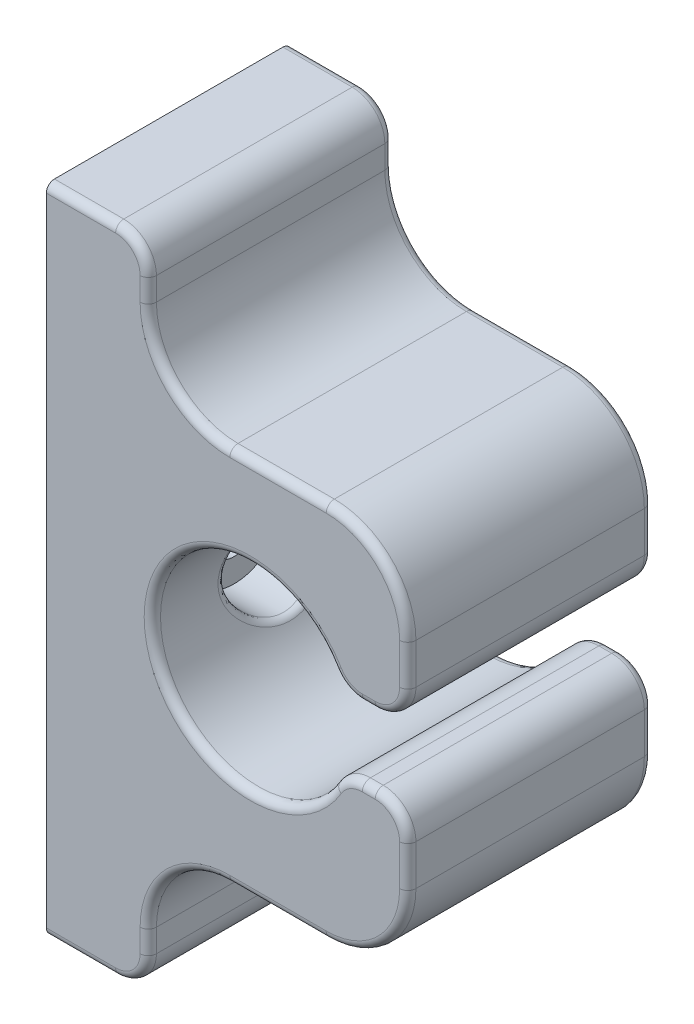
SolidWorks part; units mm, degrees
material "Plastique personnalisé"
ref_plane "Plan de face" through (0, 0, 0) normal (0, 0, 1) x (1, 0, 0)
ref_plane "Plan de dessus" through (0, 0, 0) normal (0, 1, 0) x (1, 0, 0)
ref_plane "Plan de droite" through (0, 0, 0) normal (1, 0, 0) x (0, 0, -1)
sketch "Esquisse1" plane through (0, 0, 0) normal (0, 0, 1) x (1, 0, 0)
  line L0 (0, 20) -> (12.5, 20) construction
  line L1 (0, 0) -> (4.25, 0)
  line L2 (0, 0) -> (0, 40)
  line L3 (0, 40) -> (4.25, 40)
  line L6 (20.1564, 17.9) -> (19.3695, 17.9)
  line L8 (20.1564, 22.1) -> (19.3695, 22.1)
  line L10 (11.25, 8.4118) -> (17.1564, 8.4118)
  line L12 (18.5, 20) -> (22.1564, 20) construction
  line L13 (6.25, 38) -> (6.25, 36.5882)
  line L14 (11.25, 31.5882) -> (17.1564, 31.5882)
  line L18 (6.25, 2) -> (6.25, 3.4118)
  line L19 (22.1564, 15.9) -> (22.1564, 13.4118)
  line L23 (22.1564, 26.5882) -> (22.1564, 24.1)
  arc A0 (17.6521, 23.075) -> (17.6521, 16.925) centre (12.5, 20) ccw
  arc A1 (11.25, 8.4118) -> (6.25, 3.4118) centre (11.25, 3.4118) ccw
  arc A2 (6.25, 36.5882) -> (11.25, 31.5882) centre (11.25, 36.5882) ccw
  arc A3 (17.1564, 8.4118) -> (22.1564, 13.4118) centre (17.1564, 13.4118) ccw
  arc A4 (17.1564, 31.5882) -> (22.1564, 26.5882) centre (17.1564, 26.5882) cw
  arc A5 (19.3695, 22.1) -> (17.6521, 23.075) centre (19.3695, 24.1) cw
  arc A6 (19.3695, 17.9) -> (17.6521, 16.925) centre (19.3695, 15.9) ccw
  arc A7 (20.1564, 17.9) -> (22.1564, 15.9) centre (20.1564, 15.9) cw
  arc A8 (20.1564, 22.1) -> (22.1564, 24.1) centre (20.1564, 24.1) ccw
  arc A9 (4.25, 0) -> (6.25, 2) centre (4.25, 2) ccw
  arc A10 (4.25, 40) -> (6.25, 38) centre (4.25, 38) cw
  point P9 (6.25, 8.4118)
  point P16 (6.25, 31.5882)
  point P33 (22.1564, 17.9)
  dimension "D3" = 2
  dimension "D2" = 5
  dimension "D4" = 2
  dimension "D1" = 40
extrude "Boss.-Extru.1" add sketch "Esquisse1" along normal blind 15
fillet "Congé1" radius 0.5 42 edges at (2.125, 0, 0) (5.6642, 0.5858, 0) (6.25, 2.7059, 0) (7.7145, 6.9473, 0) (14.2032, 8.4118, 0) (20.6919, 9.8763, 0) (22.1564, 14.6559, 0) (21.5706, 17.3142, 0) (19.7629, 17.9, 0) (18.3821, 17.6393, 0) (6.5, 20, 0) (18.3821, 22.3607, 0) (19.7629, 22.1, 0) (21.5706, 22.6858, 0) (22.1564, 25.3441, 0) (20.6919, 30.1237, 0) (14.2032, 31.5882, 0) (2.125, 40, 0) (5.6642, 39.4142, 0) (6.25, 37.2941, 0) (2.125, 0, 15) (5.6642, 0.5858, 15) (6.25, 2.7059, 15) (7.7145, 6.9473, 15) (14.2032, 8.4118, 15) (20.6919, 9.8763, 15) (22.1564, 14.6559, 15) (21.5706, 17.3142, 15) (19.7629, 17.9, 15) (18.3821, 17.6393, 15) (6.5, 20, 15) (18.3821, 22.3607, 15) (19.7629, 22.1, 15) (21.5706, 22.6858, 15) (22.1564, 25.3441, 15) (20.6919, 30.1237, 15) (14.2032, 31.5882, 15) (2.125, 40, 15) (5.6642, 39.4142, 15) (6.25, 37.2941, 15) (7.7145, 33.0527, 0) (7.7145, 33.0527, 15)
sketch "Esquisse2" plane through (0, 0, 0) normal (-1, 0, 0) x (0, 0, 1)
  circle A0 centre (7.48, 20) radius 1.55
extrude "Enlèv. mat.-Extru.1" cut sketch "Esquisse2" against normal blind 15
ref_plane "Plan1" through (7, 0, 0) normal (-1, 0, 0) x (0, 0, 1)
sketch "Esquisse3" plane through (7, 0, 0) normal (-1, 0, 0) x (0, 0, 1)
  circle A0 centre (7.48, 20) radius 3
extrude "Enlèv. mat.-Extru.2" cut sketch "Esquisse3" along normal blind 3 and the other way blind 3
fillet "Congé2" radius 0.5 1 edges at (6.5076, 19.6973, 4.4953)
